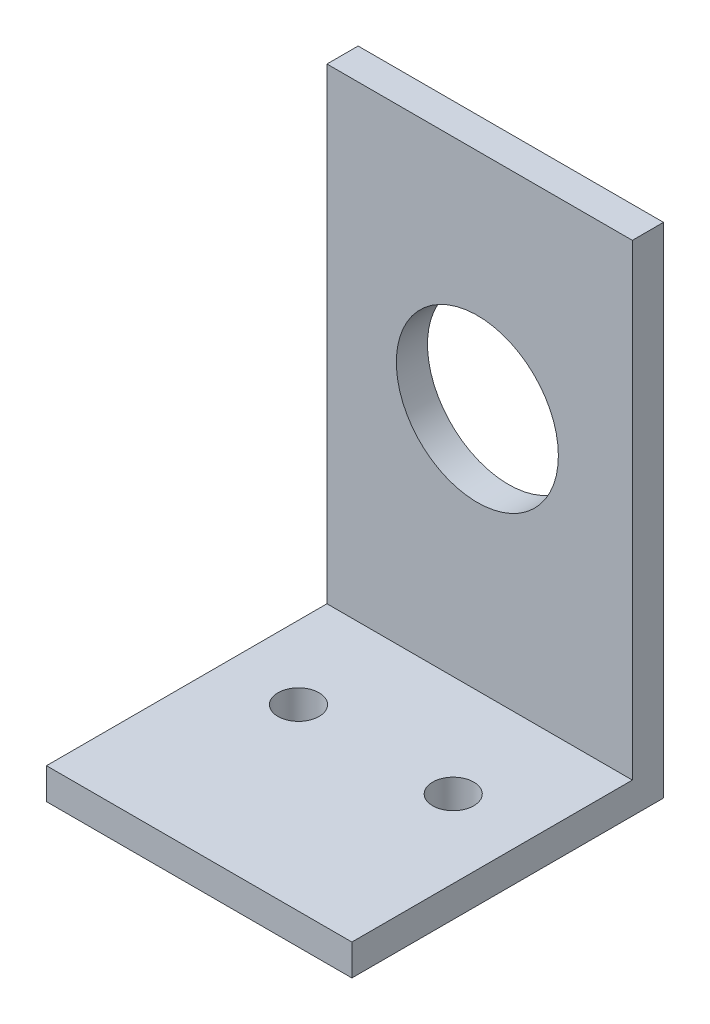
SolidWorks part; units mm, degrees
ref_plane "Plan de face" through (0, 0, 0) normal (0, 0, 1) x (1, 0, 0)
ref_plane "Plan de dessus" through (0, 0, 0) normal (0, 1, 0) x (1, 0, 0)
ref_plane "Plan de droite" through (0, 0, 0) normal (1, 0, 0) x (0, 0, -1)
sketch "Esquisse1" plane through (0, 0, 0) normal (0, 0, 1) x (1, 0, 0)
  line L1 (-24.5, -40) -> (24.5, -40)
  line L2 (-24.5, -40) -> (-24.5, 40)
  line L3 (-24.5, 40) -> (24.5, 40)
  line L4 (24.5, -40) -> (24.5, 40)
  line L5 (-24.5, -40) -> (24.5, 40) construction
  line L6 (-24.5, 40) -> (24.5, -40) construction
  point P0 (0, 0)
  dimension "D1" = 80
  dimension "D2" = 49
extrude "Boss.-Extru.1" add sketch "Esquisse1" along normal blind 50
sketch "Esquisse2" plane through (24.5, 0, 0) normal (1, 0, 0) x (0, 0, -1)
  line L8 (-5, -35) -> (-5, 35)
  line L9 (-5, 35) -> (-45, 35)
  line L10 (-45, 35) -> (-45, -35)
  line L11 (-45, -35) -> (-5, -35)
  line L12 (-5, -35) -> (-5, 55.8425)
  line L13 (-5, 55.8425) -> (-78.0043, 55.8425)
  line L14 (-78.0043, 55.8425) -> (-78.0043, -35)
  line L15 (-78.0043, -35) -> (-5, -35)
  dimension "D1" = 5
extrude "Enlèv. mat.-Extru.1" cut sketch "Esquisse2" against normal blind 101
hole_wizard "Dégagement M61" positions "Esquisse7" profile "Esquisse6" hole size "M6" standard "JIS" end condition through all
sketch "Esquisse7" plane through (0, -40, 0) normal (0, -1, 0) x (-1, 0, 0)
  point P0 (-12.0515, -21.2938)
  point P2 (12.7692, -21.2938)
sketch "Esquisse6" plane through (12.0515, -40, 21.2938) normal (1, 0, 0) x (0, 0, -1)
  line L0 (0, 0) -> (0, 80)
  line L1 (0, 80) -> (3.3, 80)
  line L2 (3.3, 80) -> (3.3, 0)
  line L5 (3.3, 0) -> (0, 0)
  line L11 (0, -6.35) -> (0, 107.95) construction
  dimension "Diamètre du perçage jusqu'au prochain" = 6.6
  dimension "Profondeur du perçage jusqu'au prochain" = 80
hole_wizard "Dégagement M241" positions "Esquisse10" profile "Esquisse8" hole size "M24" standard "JIS" end condition through all
sketch "Esquisse10" plane through (0, 0, 5) normal (0, 0, 1) x (1, 0, 0)
  point P0 (-0.37, 4.1332)
sketch "Esquisse8" plane through (-0.37, 4.1332, 5) normal (1, 0, 0) x (0, -1, 0)
  line L0 (0, 0) -> (0, 5)
  line L1 (0, 5) -> (13, 5)
  line L2 (13, 5) -> (13, 0)
  line L5 (13, 0) -> (0, 0)
  line L11 (0, -6.35) -> (0, 107.95) construction
  dimension "Diamètre du perçage jusqu'au prochain" = 26
  dimension "Profondeur du perçage jusqu'au prochain" = 5
